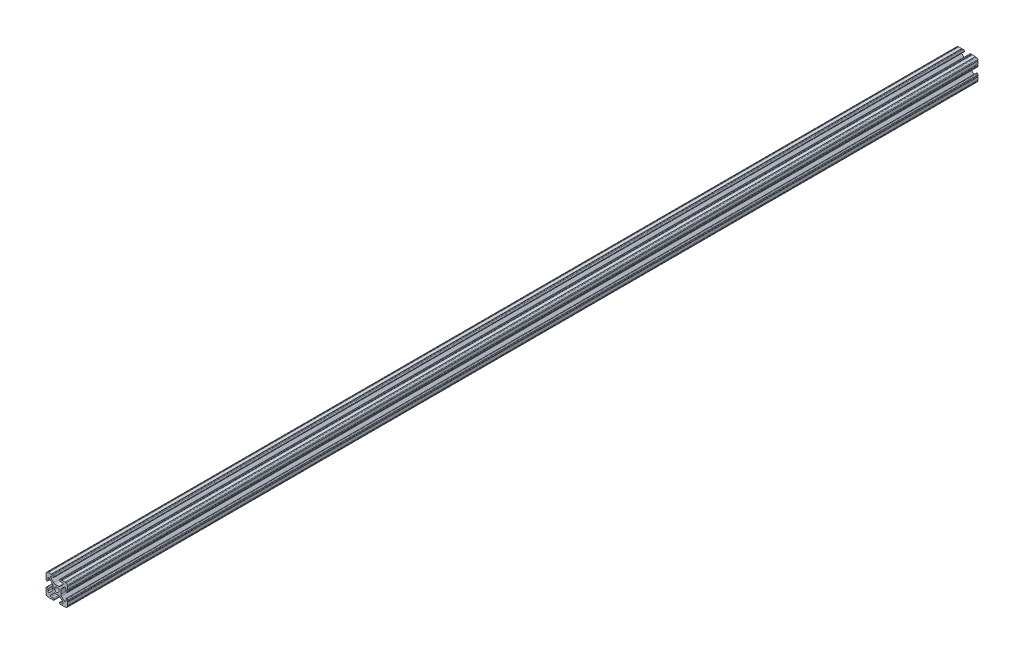
SolidWorks part; units mm, degrees
ref_plane "Front Plane" through (0, 0, 0) normal (0, 0, 1) x (1, 0, 0)
ref_plane "Top Plane" through (0, 0, 0) normal (0, 1, 0) x (1, 0, 0)
ref_plane "Right Plane" through (0, 0, 0) normal (1, 0, 0) x (0, 0, -1)
sketch "Sketch1" plane through (0, 0, 0) normal (0, 0, 1) x (1, 0, 0)
  line L0 (-3.7373, -5.2999) -> (-7.1039, -8.6665)
  line L1 (-6.3485, -10.4902) -> (-4.1904, -10.4902)
  line L2 (-3.2512, -11.4294) -> (-3.2512, -11.7608)
  line L3 (-4.1904, -12.7) -> (-5.2436, -12.7)
  line L4 (-6.3485, -12.7) -> (-9.8037, -12.7)
  line L5 (-12.7, -9.8037) -> (-12.7, -6.3485)
  line L6 (-12.7, -5.2436) -> (-12.7, -4.1904)
  line L7 (-11.7608, -3.2512) -> (-11.4294, -3.2512)
  line L8 (-10.4902, -4.1904) -> (-10.4902, -6.3485)
  line L9 (-8.6665, -7.1039) -> (-5.2999, -3.7373)
  line L10 (-4.6482, -2.164) -> (-4.6482, 2.164)
  line L11 (-8.6665, 7.1039) -> (-5.2999, 3.7373)
  line L12 (-10.4902, 4.1904) -> (-10.4902, 6.3485)
  line L13 (-11.7608, 3.2512) -> (-11.4294, 3.2512)
  line L14 (-12.7, 5.2436) -> (-12.7, 4.1904)
  line L15 (-12.7, 9.8037) -> (-12.7, 6.3485)
  line L16 (-6.3485, 12.7) -> (-9.8037, 12.7)
  line L17 (-4.1904, 12.7) -> (-5.2436, 12.7)
  line L18 (-3.2512, 11.4294) -> (-3.2512, 11.7608)
  line L19 (-6.3485, 10.4902) -> (-4.1904, 10.4902)
  line L20 (-3.7373, 5.2999) -> (-7.1039, 8.6665)
  line L21 (-2.164, 4.6482) -> (2.164, 4.6482)
  line L22 (3.7373, 5.2999) -> (7.1039, 8.6665)
  line L23 (6.3485, 10.4902) -> (4.1904, 10.4902)
  line L24 (3.2512, 11.4294) -> (3.2512, 11.7608)
  line L25 (4.1904, 12.7) -> (5.2436, 12.7)
  line L26 (6.3485, 12.7) -> (9.8037, 12.7)
  line L27 (12.7, 9.8037) -> (12.7, 6.3485)
  line L28 (12.7, 5.2436) -> (12.7, 4.1904)
  line L29 (11.7608, 3.2512) -> (11.4294, 3.2512)
  line L30 (10.4902, 4.1904) -> (10.4902, 6.3485)
  line L31 (8.6665, 7.1039) -> (5.2999, 3.7373)
  line L32 (3.2512, -11.4294) -> (3.2512, -11.7608)
  line L33 (6.3485, -10.4902) -> (4.1904, -10.4902)
  line L34 (3.7373, -5.2999) -> (7.1039, -8.6665)
  line L35 (-2.164, -4.6482) -> (2.164, -4.6482)
  line L36 (4.6482, -2.164) -> (4.6482, 2.164)
  line L37 (8.6665, -7.1039) -> (5.2999, -3.7373)
  line L38 (10.4902, -4.1904) -> (10.4902, -6.3485)
  line L39 (11.7608, -3.2512) -> (11.4294, -3.2512)
  line L40 (12.7, -5.2436) -> (12.7, -4.1904)
  line L41 (6.3485, -12.7) -> (9.8037, -12.7)
  line L42 (12.7, -9.8037) -> (12.7, -6.3485)
  line L43 (4.1904, -12.7) -> (5.2436, -12.7)
  circle A0 centre (0, 0) radius 2.6035
  arc A1 (12.7, -9.8037) -> (12.58, -10.8954) centre (12.7, -10.3562) ccw
  arc A2 (10.8954, -12.58) -> (9.8037, -12.7) centre (10.3562, -12.7) ccw
  arc A3 (6.3485, -12.7) -> (5.2436, -12.7) centre (5.796, -12.7) ccw
  arc A4 (-2.164, -4.6482) -> (-3.7373, -5.2999) centre (-2.164, -6.8732) ccw
  arc A5 (-7.1039, -8.6665) -> (-6.3485, -10.4902) centre (-6.3485, -9.4219) ccw
  arc A6 (-3.2512, -11.4294) -> (-4.1904, -10.4902) centre (-4.1904, -11.4294) ccw
  arc A7 (-4.1904, -12.7) -> (-3.2512, -11.7608) centre (-4.1904, -11.7608) ccw
  arc A8 (-5.2436, -12.7) -> (-6.3485, -12.7) centre (-5.796, -12.7) ccw
  arc A9 (-9.8037, -12.7) -> (-10.8954, -12.58) centre (-10.3562, -12.7) ccw
  arc A10 (-12.58, -10.8954) -> (-10.8954, -12.58) centre (-10.1173, -10.1173) ccw
  arc A11 (-12.58, -10.8954) -> (-12.7, -9.8037) centre (-12.7, -10.3562) ccw
  arc A12 (-12.7, -6.3485) -> (-12.7, -5.2436) centre (-12.7, -5.796) ccw
  arc A13 (-11.7608, -3.2512) -> (-12.7, -4.1904) centre (-11.7608, -4.1904) ccw
  arc A14 (-10.4902, -4.1904) -> (-11.4294, -3.2512) centre (-11.4294, -4.1904) ccw
  arc A15 (-10.4902, -6.3485) -> (-8.6665, -7.1039) centre (-9.4219, -6.3485) ccw
  arc A16 (-5.2999, -3.7373) -> (-4.6482, -2.164) centre (-6.8732, -2.164) ccw
  arc A17 (-4.6482, 2.164) -> (-5.2999, 3.7373) centre (-6.8732, 2.164) ccw
  arc A18 (-8.6665, 7.1039) -> (-10.4902, 6.3485) centre (-9.4219, 6.3485) ccw
  arc A19 (-11.4294, 3.2512) -> (-10.4902, 4.1904) centre (-11.4294, 4.1904) ccw
  arc A20 (-12.7, 4.1904) -> (-11.7608, 3.2512) centre (-11.7608, 4.1904) ccw
  arc A21 (-12.7, 5.2436) -> (-12.7, 6.3485) centre (-12.7, 5.796) ccw
  arc A22 (-12.7, 9.8037) -> (-12.58, 10.8954) centre (-12.7, 10.3562) ccw
  arc A23 (-10.8954, 12.58) -> (-12.58, 10.8954) centre (-10.1173, 10.1173) ccw
  arc A24 (-10.8954, 12.58) -> (-9.8037, 12.7) centre (-10.3562, 12.7) ccw
  arc A25 (-6.3485, 12.7) -> (-5.2436, 12.7) centre (-5.796, 12.7) ccw
  arc A26 (-3.2512, 11.7608) -> (-4.1904, 12.7) centre (-4.1904, 11.7608) ccw
  arc A27 (-4.1904, 10.4902) -> (-3.2512, 11.4294) centre (-4.1904, 11.4294) ccw
  arc A28 (-6.3485, 10.4902) -> (-7.1039, 8.6665) centre (-6.3485, 9.4219) ccw
  arc A29 (-3.7373, 5.2999) -> (-2.164, 4.6482) centre (-2.164, 6.8732) ccw
  arc A30 (2.164, 4.6482) -> (3.7373, 5.2999) centre (2.164, 6.8732) ccw
  arc A31 (7.1039, 8.6665) -> (6.3485, 10.4902) centre (6.3485, 9.4219) ccw
  arc A32 (3.2512, 11.4294) -> (4.1904, 10.4902) centre (4.1904, 11.4294) ccw
  arc A33 (4.1904, 12.7) -> (3.2512, 11.7608) centre (4.1904, 11.7608) ccw
  arc A34 (5.2436, 12.7) -> (6.3485, 12.7) centre (5.796, 12.7) ccw
  arc A35 (9.8037, 12.7) -> (10.8954, 12.58) centre (10.3562, 12.7) ccw
  arc A36 (12.58, 10.8954) -> (10.8954, 12.58) centre (10.1173, 10.1173) ccw
  arc A37 (12.58, 10.8954) -> (12.7, 9.8037) centre (12.7, 10.3562) ccw
  arc A38 (12.7, 6.3485) -> (12.7, 5.2436) centre (12.7, 5.796) ccw
  arc A39 (11.7608, 3.2512) -> (12.7, 4.1904) centre (11.7608, 4.1904) ccw
  arc A40 (10.4902, 4.1904) -> (11.4294, 3.2512) centre (11.4294, 4.1904) ccw
  arc A41 (10.4902, 6.3485) -> (8.6665, 7.1039) centre (9.4219, 6.3485) ccw
  arc A42 (5.2999, 3.7373) -> (4.6482, 2.164) centre (6.8732, 2.164) ccw
  arc A43 (12.7, -5.2436) -> (12.7, -6.3485) centre (12.7, -5.796) ccw
  arc A44 (4.1904, -10.4902) -> (3.2512, -11.4294) centre (4.1904, -11.4294) ccw
  arc A45 (6.3485, -10.4902) -> (7.1039, -8.6665) centre (6.3485, -9.4219) ccw
  arc A46 (3.7373, -5.2999) -> (2.164, -4.6482) centre (2.164, -6.8732) ccw
  arc A47 (4.6482, -2.164) -> (5.2999, -3.7373) centre (6.8732, -2.164) ccw
  arc A48 (8.6665, -7.1039) -> (10.4902, -6.3485) centre (9.4219, -6.3485) ccw
  arc A49 (11.4294, -3.2512) -> (10.4902, -4.1904) centre (11.4294, -4.1904) ccw
  arc A50 (12.7, -4.1904) -> (11.7608, -3.2512) centre (11.7608, -4.1904) ccw
  arc A51 (10.8954, -12.58) -> (12.58, -10.8954) centre (10.1173, -10.1173) ccw
  arc A52 (3.2512, -11.7608) -> (4.1904, -12.7) centre (4.1904, -11.7608) ccw
extrude "Boss-Extrude1" add sketch "Sketch1" along normal blind 1066.8
ref_plane "Plane1" through (0, 0, 533.4) normal (0, 0, -1) x (-1, 0, 0)
